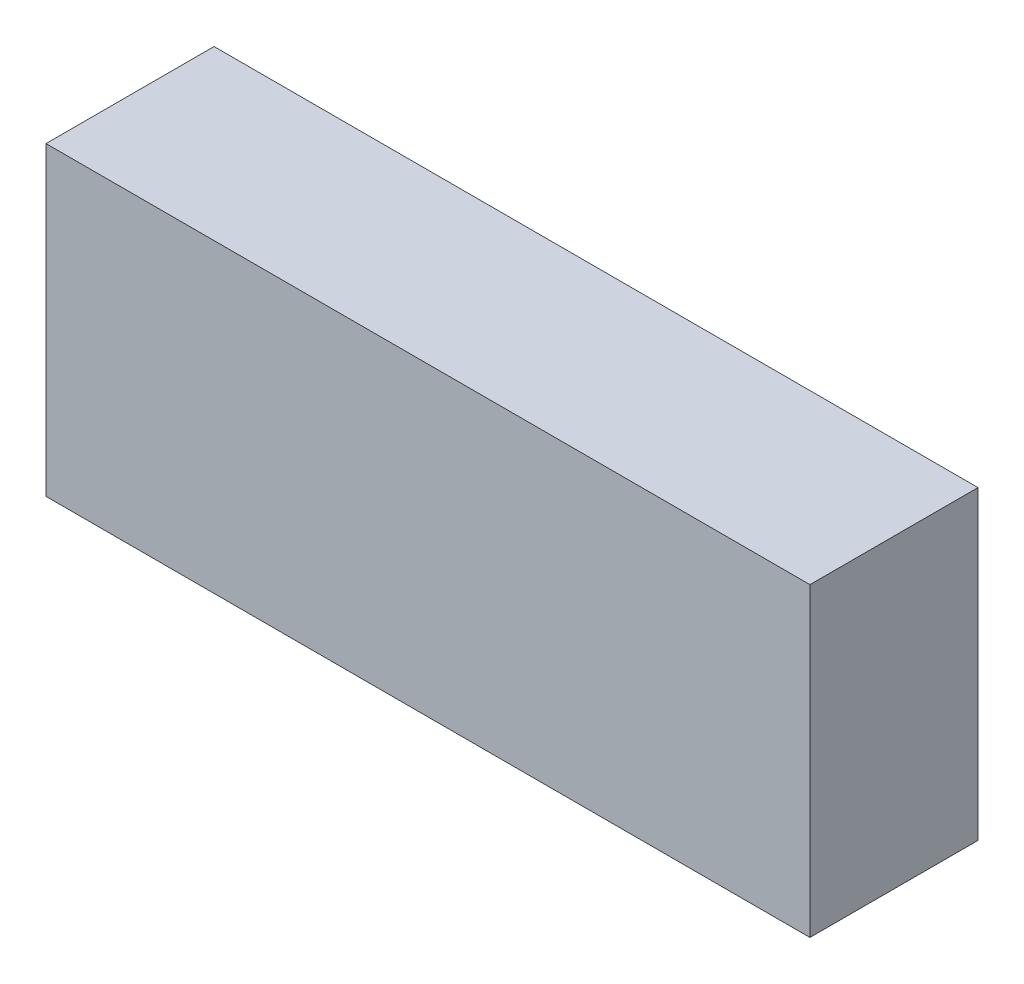
SolidWorks part; units mm, degrees
ref_plane "Front Plane" through (0, 0, 0) normal (0, 0, 1) x (1, 0, 0)
ref_plane "Top Plane" through (0, 0, 0) normal (0, 1, 0) x (1, 0, 0)
ref_plane "Right Plane" through (0, 0, 0) normal (1, 0, 0) x (0, 0, -1)
sketch "Sketch1" plane through (0, 0, 0) normal (0, 0, 1) x (1, 0, 0)
  line L1 (0, 0) -> (100, 0)
  line L2 (0, 0) -> (0, -40)
  line L3 (0, -40) -> (100, -40)
  line L4 (100, 0) -> (100, -40)
  dimension "D1" = 40
  dimension "D2" = 100
extrude "Boss-Extrude1" add sketch "Sketch1" along normal blind 22
